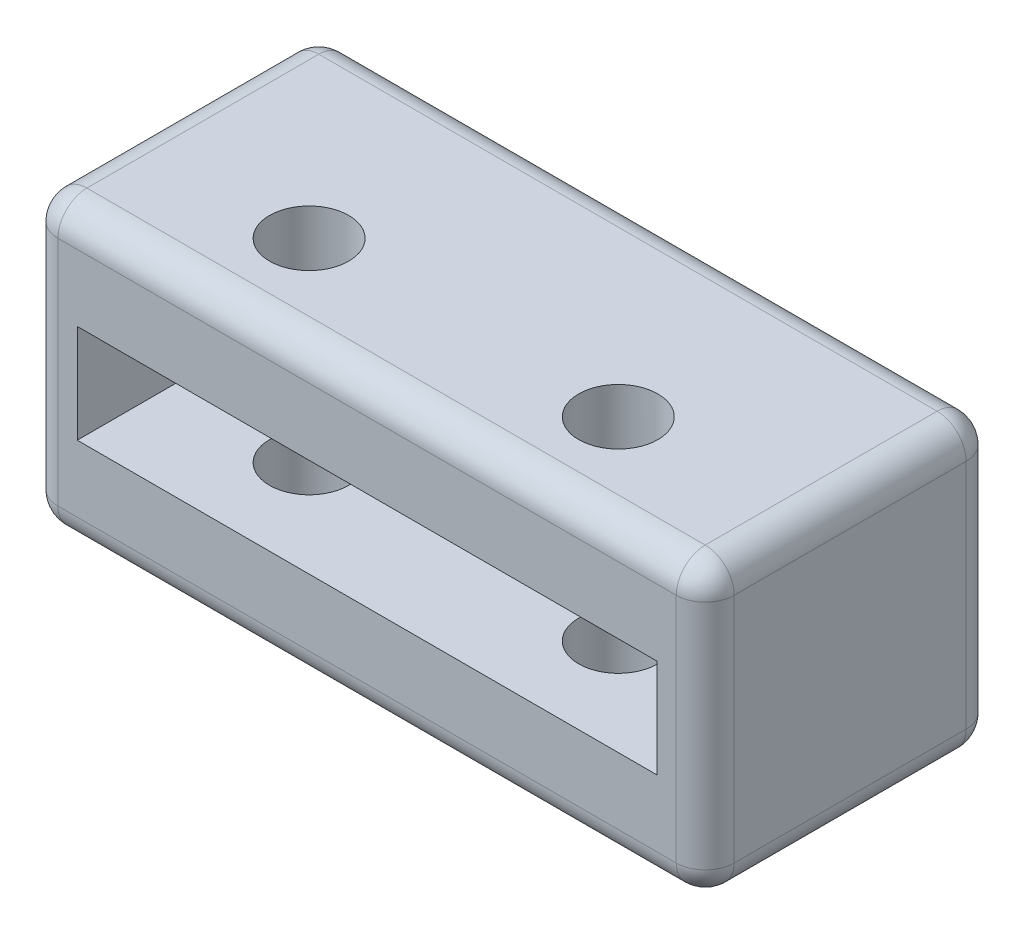
SolidWorks part; units mm, degrees
ref_plane "Plan de face" through (0, 0, 0) normal (0, 0, 1) x (1, 0, 0)
ref_plane "Plan de dessus" through (0, 0, 0) normal (0, 1, 0) x (1, 0, 0)
ref_plane "Plan de droite" through (0, 0, 0) normal (1, 0, 0) x (0, 0, -1)
sketch "Esquisse1" plane through (0, 0, 0) normal (1, 0, 0) x (0, 0, -1)
  line L0 (-5.1072, 0) -> (13.2475, 0) construction
  line L10 (6, 7.5) -> (-6, 7.5)
  line L11 (7.5, 6) -> (7.5, -6)
  line L12 (6, -7.5) -> (-6, -7.5)
  line L13 (-7.5, 6) -> (-7.5, -6)
  line L14 (7.5, 7.5) -> (-7.5, -7.5) construction
  line L15 (7.5, -7.5) -> (-7.5, 7.5) construction
  arc A4 (6, 7.5) -> (7.5, 6) centre (6, 6) cw
  arc A5 (7.5, -6) -> (6, -7.5) centre (6, -6) cw
  arc A6 (-6, -7.5) -> (-7.5, -6) centre (-6, -6) cw
  arc A7 (-6, 7.5) -> (-7.5, 6) centre (-6, 6) ccw
  point P3 (0, 0)
  dimension "D3" = 1.5
  dimension "D1" = 15
  dimension "D2" = 15
extrude "Boss.-Extru.1" add sketch "Esquisse1" along normal blind 35
sketch "Esquisse2" plane through (0, 0, 7.5) normal (0, 0, 1) x (1, 0, 0)
  line L0 (-0.5668, 0) -> (41.8026, 0) construction
  line L2 (32.5, 2.55) -> (2.5, 2.55)
  line L3 (32.5, 2.55) -> (32.5, -2.55)
  line L4 (32.5, -2.55) -> (2.5, -2.55)
  line L5 (2.5, 2.55) -> (2.5, -2.55)
  line L6 (32.5, 2.55) -> (2.5, -2.55) construction
  line L7 (32.5, -2.55) -> (2.5, 2.55) construction
  line L9 (0, 6) -> (0, -6) construction
  point P3 (17.5, 0)
  dimension "D1" = 30
  dimension "D2" = 5.1
  dimension "D3" = 17.5
extrude "Enlèv. mat.-Extru.1" cut sketch "Esquisse2" against normal blind 10
sketch "Esquisse3" plane through (0, -2.55, 0) normal (0, 1, 0) x (1, 0, 0)
  line L0 (2.5, -2.5) -> (32.5, -2.5) construction
  line L1 (17.5, 2.5) -> (17.5, -6) construction
  line L2 (35, -6) -> (0, -6) construction
  line L4 (2.5, -7.5) -> (32.5, -7.5)
  line L5 (32.5, -7.5) -> (32.5, 2.5)
  line L6 (32.5, 2.5) -> (2.5, 2.5)
  line L7 (2.5, 2.5) -> (2.5, -7.5)
  line L8 (2.5, -7.5) -> (32.5, -7.5)
  line L9 (32.5, -7.5) -> (32.5, 2.5)
  line L10 (32.5, 2.5) -> (2.5, 2.5)
  line L11 (2.5, 2.5) -> (2.5, -7.5)
  circle A0 centre (9.5, -2.5) radius 2.05
  circle A2 centre (25.5, -2.5) radius 2.05
  dimension "D2" = 4.1
  dimension "D3" = 8
  dimension "D1" = 0
extrude "Enlèv. mat.-Extru.2" cut sketch "Esquisse3" against normal through all both and the other way through all contours A0 | A2
fillet "Congé1" radius 1.5 16 edges at (35, 7.0607, 7.0607) (35, 7.5, 0) (35, 7.0607, -7.0607) (35, 0, -7.5) (35, -7.0607, -7.0607) (35, -7.5, 0) (35, -7.0607, 7.0607) (0, 7.0607, 7.0607) (0, 7.5, 0) (0, 7.0607, -7.0607) (0, 0, -7.5) (0, -7.0607, -7.0607) (0, -7.5, 0) (0, -7.0607, 7.0607) (35, 0, 7.5) (0, 0, 7.5)
